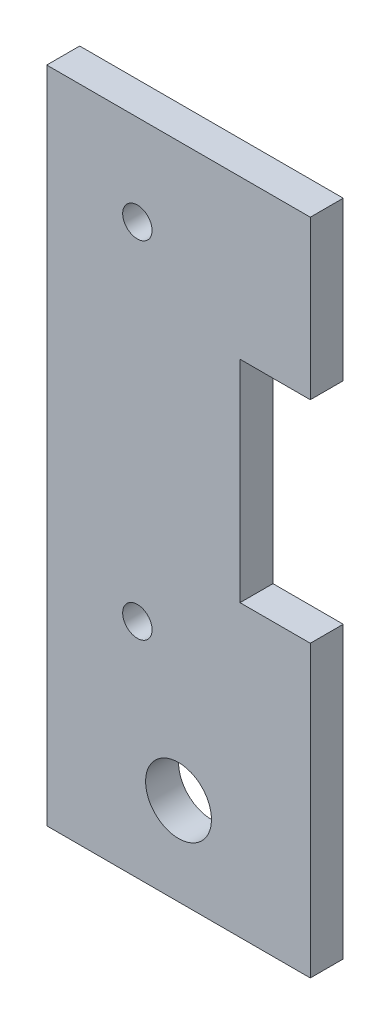
SolidWorks part; units mm, degrees
ref_plane "Front Plane" through (0, 0, 0) normal (0, 0, 1) x (1, 0, 0)
ref_plane "Top Plane" through (0, 0, 0) normal (0, 1, 0) x (1, 0, 0)
ref_plane "Right Plane" through (0, 0, 0) normal (1, 0, 0) x (0, 0, -1)
sketch "Sketch2" plane through (0, 0, 0) normal (0, 0, 1) x (1, 0, 0)
  line L1 (0, 38.1) -> (-38.1, 38.1)
  line L2 (0, 38.1) -> (0, -57.15)
  line L3 (0, -57.15) -> (-38.1, -57.15)
  line L4 (-38.1, 38.1) -> (-38.1, -57.15)
  dimension "D1" = 38.1
  dimension "D2" = 95.25
  dimension "D3" = 38.1
extrude "Boss-Extrude1" add sketch "Sketch2" along normal blind 4.7625
sketch "Sketch3" plane through (0, 0, 0) normal (0, 0, 1) x (1, 0, 0)
  line L0 (0, -57.15) -> (-38.1, -57.15) construction
  line L1 (0, -57.15) -> (0, 38.1) construction
  line L2 (0, 15.24) -> (-10.16, 15.24)
  line L3 (0, 15.24) -> (0, -15.24)
  line L4 (0, -15.24) -> (-10.16, -15.24)
  line L5 (-10.16, 15.24) -> (-10.16, -15.24)
  circle A1 centre (-25, 25) radius 2.125
  circle A2 centre (25, 25) radius 2.125
  circle A3 centre (25, -25) radius 2.125
  circle A4 centre (-25, -25) radius 2.125
  circle A5 centre (-19.05, -44.45) radius 4.7625
  point P2 (-25, -25)
  point P5 (25, -25)
  point P12 (25, 25)
  point P15 (-25, 25)
  point P21 (-19.05, -57.15)
  point P24 (0, 0)
  dimension "D3" = 30.48
  dimension "D5" = 4.25
  dimension "D6" = 25
  dimension "D8" = 9.525
  dimension "D1" = 50
  dimension "D2" = 50
  dimension "D4" = 10.16
  dimension "D7" = 12.7
  dimension "D9" = 25
extrude "Cut-Extrude3" cut sketch "Sketch3" along normal through all
